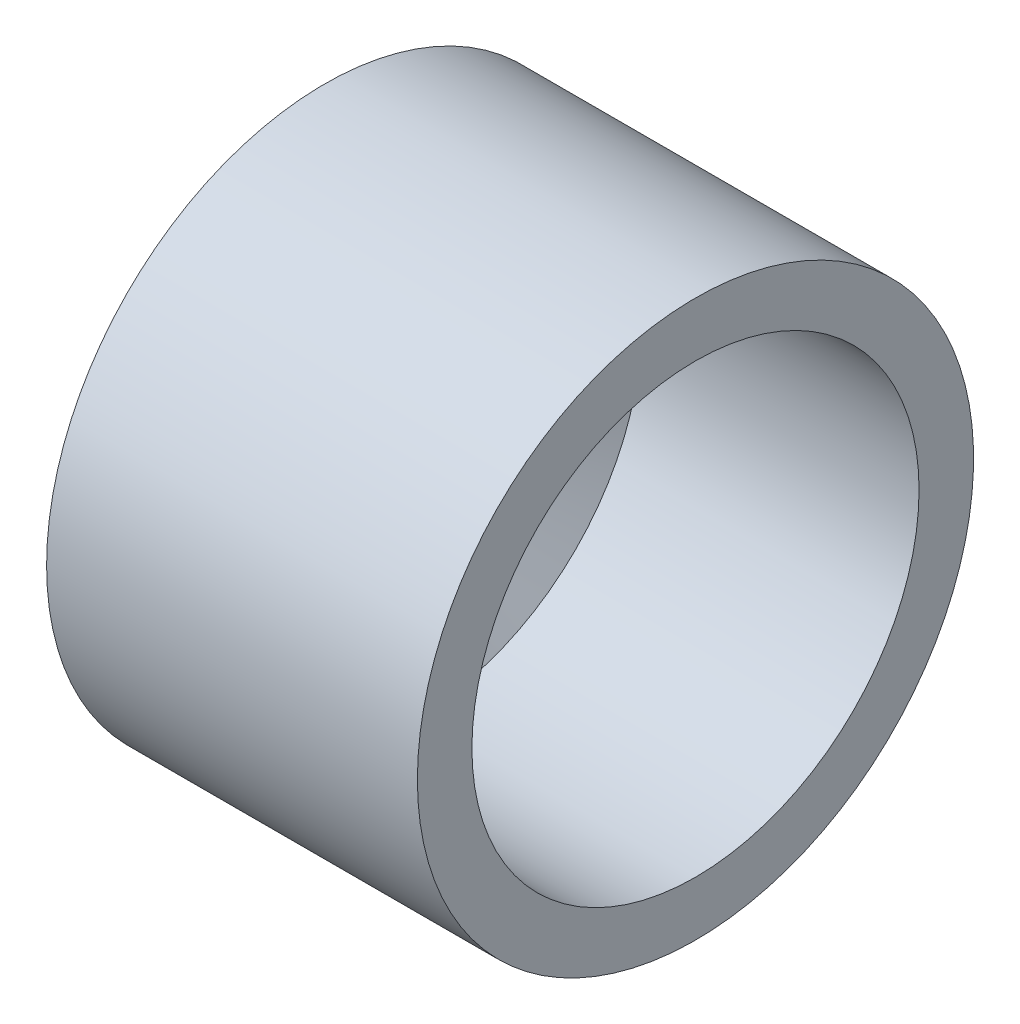
SolidWorks part; units mm, degrees
ref_plane "Front Plane" through (0, 0, 0) normal (0, 0, 1) x (1, 0, 0)
ref_plane "Top Plane" through (0, 0, 0) normal (0, 1, 0) x (1, 0, 0)
ref_plane "Right Plane" through (0, 0, 0) normal (1, 0, 0) x (0, 0, -1)
sketch "Sketch1" plane through (0, 0, 0) normal (0, 0, 1) x (1, 0, 0)
  line L0 (0, 0) -> (20.3021, 0) construction
  line L1 (0, 9.525) -> (12.7, 9.525)
  line L2 (12.7, 9.525) -> (12.7, 0)
  line L5 (12.7, 0) -> (0.889, 0)
  line L6 (0, 8.255) -> (0, 9.525)
  line L7 (0.889, 0) -> (0.889, 8.255)
  line L8 (0.889, 8.255) -> (0, 8.255)
  point P7 (10.8289, 1.2224)
  dimension "D1" = 12.7
  dimension "D2" = 19.05
  dimension "D3" = 16.51
  dimension "D4" = 0.889
revolve "Revolve1" add sketch "Sketch1" angle 360 about L0
sketch "Sketch2" plane through (0.889, 0, 0) normal (-1, 0, 0) x (0, 0, 1)
  line L0 (0, -2.54) -> (0, 2.54) construction
  line L1 (-4.7625, -2.54) -> (-4.7625, 2.54)
  line L2 (4.7625, -2.54) -> (4.7625, 2.54)
  arc A0 (-4.7625, -2.54) -> (4.7625, -2.54) centre (0, -2.54) ccw
  arc A1 (4.7625, 2.54) -> (-4.7625, 2.54) centre (0, 2.54) ccw
  point P2 (0, 0)
  dimension "D1" = 4.7625
  dimension "D2" = 5.08
extrude "Cut-Extrude1" cut sketch "Sketch2" against normal through all
hole_wizard "3/8-18 NPSM Tapped Hole1" positions "Sketch4" profile "Sketch6" tap size "3/8-18 NPSM" standard "ANSI Inch"
sketch "Sketch4" plane through (12.7, 0, 0) normal (1, 0, 0) x (0, 0, -1)
  point P0 (0, 0)
sketch "Sketch6" plane through (12.7, 0, 0) normal (0, 1, 0) x (0, 0, -1)
  line L0 (0, 0) -> (0, 14.1265)
  line L1 (0, 14.1265) -> (7.6581, 9.525)
  line L2 (7.6581, 9.525) -> (7.6581, 0)
  line L5 (7.6581, 0) -> (0, 0)
  line L10 (0, 14.1265) -> (-7.6581, 9.525) construction
  line L11 (0, -6.35) -> (0, 107.95) construction
  dimension "Tap Drill Dia." = 15.3162
  dimension "Tap Drill Depth" = 9.525
  dimension "Drill Angle" = 118
cosmetic thread "Hole Thread1" parameters "D1"=33.6296, "D2"=16.8148
